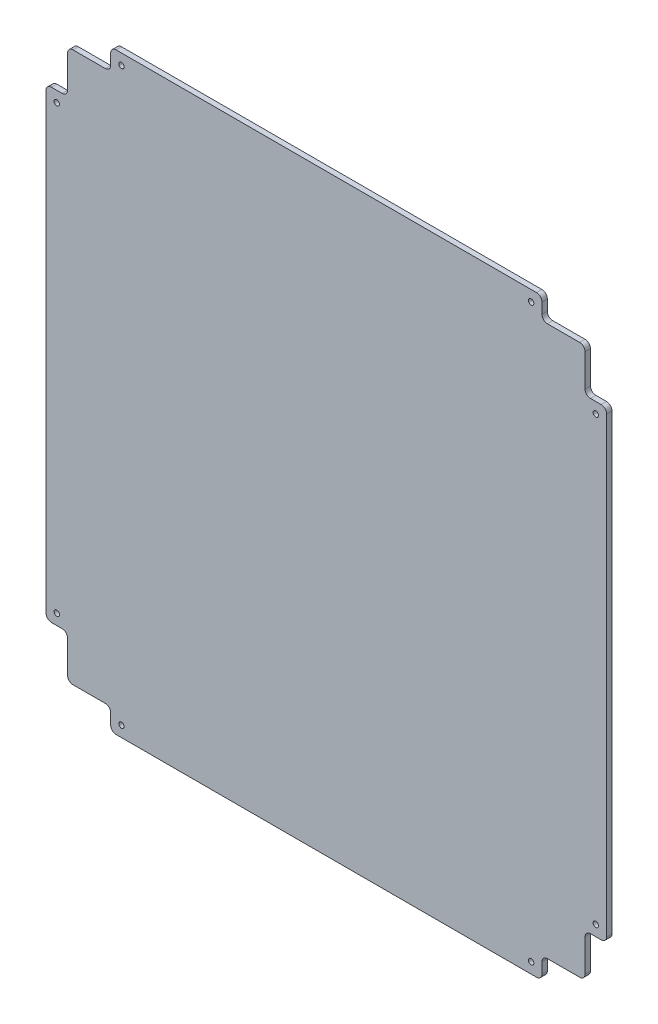
SolidWorks part; units mm, degrees
material "丙烯酸(中高冲击)"
ref_plane "前视基准面" through (0, 0, 0) normal (0, 0, 1) x (1, 0, 0)
ref_plane "上视基准面" through (0, 0, 0) normal (0, 1, 0) x (1, 0, 0)
ref_plane "右视基准面" through (0, 0, 0) normal (1, 0, 0) x (0, 0, -1)
sketch "草图1" plane through (0, 0, 0) normal (0, 0, 1) x (1, 0, 0)
  line L1 (-260, 275) -> (260, 275)
  line L2 (-260, 275) -> (-260, -275)
  line L3 (-260, -275) -> (260, -275)
  line L4 (260, 275) -> (260, -275)
  line L5 (-260, 275) -> (260, -275) construction
  line L6 (-260, -275) -> (260, 275) construction
  point P0 (0, 0)
  dimension "D1" = 550
  dimension "D2" = 520
extrude "凸台-拉伸1" add sketch "草图1" along normal blind 5
sketch "草图2" plane through (0, 0, 5) normal (0, 0, 1) x (1, 0, 0)
  line L0 (240, 255) -> (200, 255)
  line L1 (-240, 255) -> (-240, 215)
  line L2 (-240, -255) -> (-200, -255)
  line L3 (240, -255) -> (240, -215)
  line L4 (260, -275) -> (260, 275)
  line L5 (260, 275) -> (-260, 275)
  line L6 (-260, 275) -> (-260, -275)
  line L7 (-260, -275) -> (260, -275)
  line L8 (260, -275) -> (260, -215)
  line L9 (260, 275) -> (200, 275)
  line L10 (-260, 275) -> (-260, 215)
  line L11 (-260, -275) -> (-200, -275)
  line L12 (-200, 275) -> (-200, 255)
  line L13 (200, 275) -> (200, 255)
  line L14 (240, 215) -> (260, 215)
  line L15 (240, -215) -> (260, -215)
  line L16 (-200, -255) -> (-200, -275)
  line L17 (200, -255) -> (200, -275)
  line L18 (-240, -215) -> (-260, -215)
  line L19 (-240, 215) -> (-260, 215)
  line L20 (-260, -215) -> (-260, -275)
  line L21 (-260, 275) -> (-260, -275) construction
  line L22 (-240, -215) -> (-240, -255)
  line L23 (-240, 255) -> (-240, -255) construction
  line L24 (240, 215) -> (240, 255)
  line L25 (240, -255) -> (240, 255) construction
  line L26 (260, 215) -> (260, 275)
  line L27 (260, -275) -> (260, 275) construction
  line L28 (200, -275) -> (260, -275)
  line L29 (-260, -275) -> (260, -275) construction
  line L30 (200, -255) -> (240, -255)
  line L31 (-240, -255) -> (240, -255) construction
  line L32 (-200, 255) -> (-240, 255)
  line L33 (240, 255) -> (-240, 255) construction
  line L34 (-200, 275) -> (-260, 275)
  line L35 (260, 275) -> (-260, 275) construction
  circle A0 centre (-190, 265) radius 2.5
  circle A1 centre (190, 265) radius 2.5
  circle A2 centre (250, 205) radius 2.5
  circle A3 centre (-250, 205) radius 2.5
  circle A4 centre (-250, -205) radius 2.5
  circle A5 centre (-190, -265) radius 2.5
  circle A6 centre (190, -265) radius 2.5
  circle A7 centre (250, -205) radius 2.5
  dimension "D10" = 5
  dimension "D11" = 10
  dimension "D12" = 10
  dimension "D13" = 5
  dimension "D14" = 10
  dimension "D16" = 5
  dimension "D17" = 10
  dimension "D19" = 5
  dimension "D20" = 10
  dimension "D21" = 10
  dimension "D22" = 5
  dimension "D24" = 10
  dimension "D25" = 5
  dimension "D26" = 10
  dimension "D27" = 10
  dimension "D28" = 5
  dimension "D29" = 10
  dimension "D30" = 10
  dimension "D31" = 5
  dimension "D3" = 60
  dimension "D4" = 60
  dimension "D5" = 60
  dimension "D6" = 60
  dimension "D7" = 60
  dimension "D8" = 60
  dimension "D9" = 60
  dimension "D15" = 10
  dimension "D18" = 10
  dimension "D23" = 10
  dimension "D32" = 10
  dimension "D33" = 10
  dimension "D1" = 0
  dimension "D2" = 20
extrude "切除-拉伸2" cut sketch "草图2" against normal through all
fillet "圆角2" radius 5 20 edges at (-200, 275, 2.5) (-200, 255, 2.5) (-240, 255, 2.5) (-240, 215, 2.5) (-260, 215, 2.5) (-260, -215, 2.5) (-240, -215, 2.5) (-240, -255, 2.5) (-200, -255, 2.5) (-200, -275, 2.5) (200, -275, 2.5) (200, -255, 2.5) (240, -255, 2.5) (240, -215, 2.5) (260, -215, 2.5) (260, 215, 2.5) (200, 275, 2.5) (200, 255, 2.5) (240, 215, 2.5) (240, 255, 2.5)
